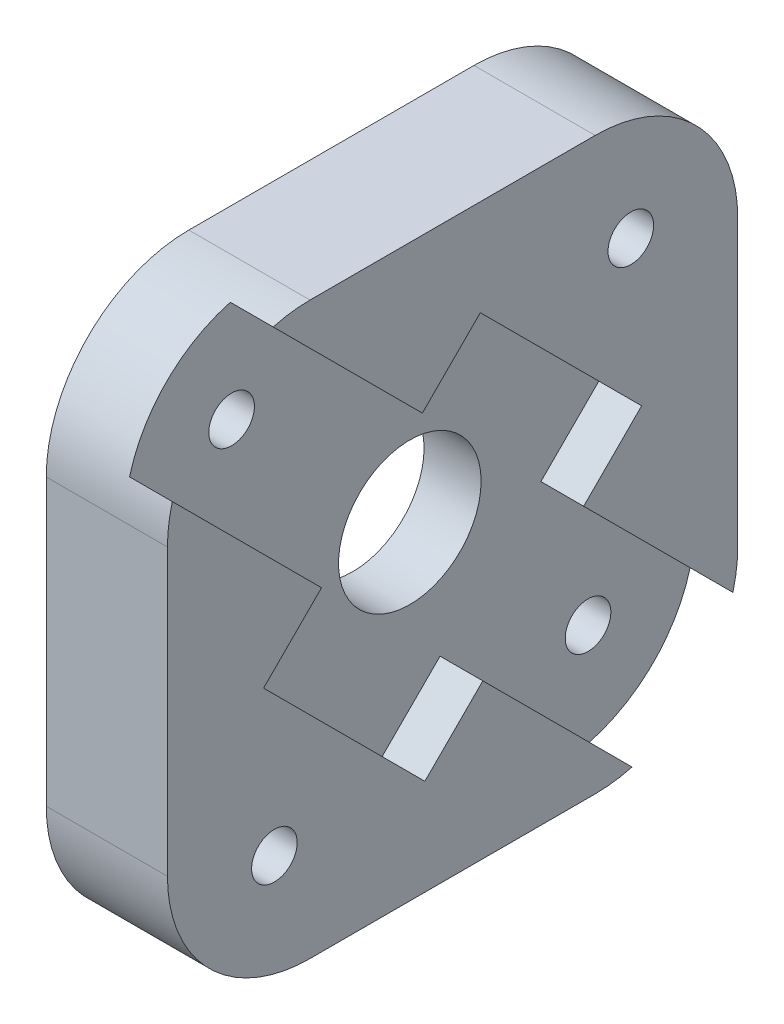
SolidWorks part; units mm, degrees
ref_plane "Front Plane" through (0, 0, 0) normal (0, 0, 1) x (1, 0, 0)
ref_plane "Top Plane" through (0, 0, 0) normal (0, 1, 0) x (1, 0, 0)
ref_plane "Right Plane" through (0, 0, 0) normal (1, 0, 0) x (0, 0, -1)
sketch "Sketch1" plane through (0, 0, 0) normal (1, 0, 0) x (0, 0, -1)
  line L1 (20, -20) -> (-20, -20)
  line L2 (20, -20) -> (20, 20)
  line L3 (20, 20) -> (-20, 20)
  line L4 (-20, -20) -> (-20, 20)
  line L5 (20, -20) -> (-20, 20) construction
  line L6 (20, 20) -> (-20, -20) construction
  point P0 (0, 0)
  dimension "D1" = 40
  dimension "D2" = 40
extrude "Boss-Extrude1" add sketch "Sketch1" along normal blind 8.5
fillet "Fillet1" radius 10
sketch "Sketch2" plane through (8.5, 0, 0) normal (1, 0, 0) x (0, 0, -1)
  line L0 (-1.9445, -13.2583) -> (13.2583, 1.9445)
  line L5 (-1.9445, -13.2583) -> (-13.2583, -1.9445)
  line L6 (13.2583, 1.9445) -> (1.9445, 13.2583)
  line L7 (-13.2583, -1.9445) -> (1.9445, 13.2583)
  line L8 (-1.9445, -13.2583) -> (1.9445, 13.2583) construction
  line L9 (13.2583, 1.9445) -> (-13.2583, -1.9445) construction
  line L10 (7.6014, 7.6014) -> (0, 0) construction
  line L11 (0, 0) -> (0, 20) construction
  line L12 (10, 20) -> (-10, 20) construction
  point P1 (0, 0)
  dimension "D1" = 16
  dimension "D2" = 21.5
  dimension "D3" = 45
extrude "Cut-Extrude1" cut sketch "Sketch2" against normal blind 3
sketch "Sketch4" plane through (5.5, 0, 0) normal (1, 0, 0) x (0, 0, -1)
  circle A0 centre (0, 0) radius 5
  dimension "D1" = 10
extrude "Cut-Extrude2" cut sketch "Sketch4" against normal through all
sketch "Sketch5" plane through (8.5, 0, 0) normal (1, 0, 0) x (0, 0, -1)
  line L1 (12.5, -12.5) -> (-12.5, -12.5) construction
  line L2 (12.5, -12.5) -> (12.5, 12.5) construction
  line L3 (12.5, 12.5) -> (-12.5, 12.5) construction
  line L4 (-12.5, -12.5) -> (-12.5, 12.5) construction
  line L5 (12.5, -12.5) -> (-12.5, 12.5) construction
  line L6 (12.5, 12.5) -> (-12.5, -12.5) construction
  circle A0 centre (-12.5, 12.5) radius 1.6
  circle A1 centre (-12.5, -12.5) radius 1.6
  circle A2 centre (12.5, -12.5) radius 1.6
  circle A3 centre (12.5, 12.5) radius 1.6
  point P0 (0, 0)
  dimension "D3" = 3.2
  dimension "D1" = 25
  dimension "D2" = 25
extrude "Cut-Extrude3" cut sketch "Sketch5" against normal through all
sketch "Sketch7" plane through (8.5, 0, 0) normal (1, 0, 0) x (0, 0, -1)
  line L0 (14.1421, -21.2132) -> (-21.2132, 14.1421)
  line L1 (14.1421, -21.2132) -> (21.2132, -14.1421)
  line L2 (-21.2132, 14.1421) -> (-14.1421, 21.2132)
  line L3 (21.2132, -14.1421) -> (-14.1421, 21.2132)
  line L4 (14.1421, -21.2132) -> (-14.1421, 21.2132) construction
  line L5 (-21.2132, 14.1421) -> (21.2132, -14.1421) construction
  line L6 (-17.6777, 17.6777) -> (-12.5, 12.5) construction
  point P1 (0, 0)
  dimension "D1" = 10
  dimension "D2" = 50
extrude "Cut-Extrude4" cut sketch "Sketch7" against normal blind 3
sketch "Sketch8" plane through (0, 0, 0) normal (-1, 0, 0) x (0, 0, 1)
  circle A0 centre (0, 0) radius 12.5
  dimension "D1" = 25
extrude "Cut-Extrude5" cut sketch "Sketch8" against normal blind 1.5
